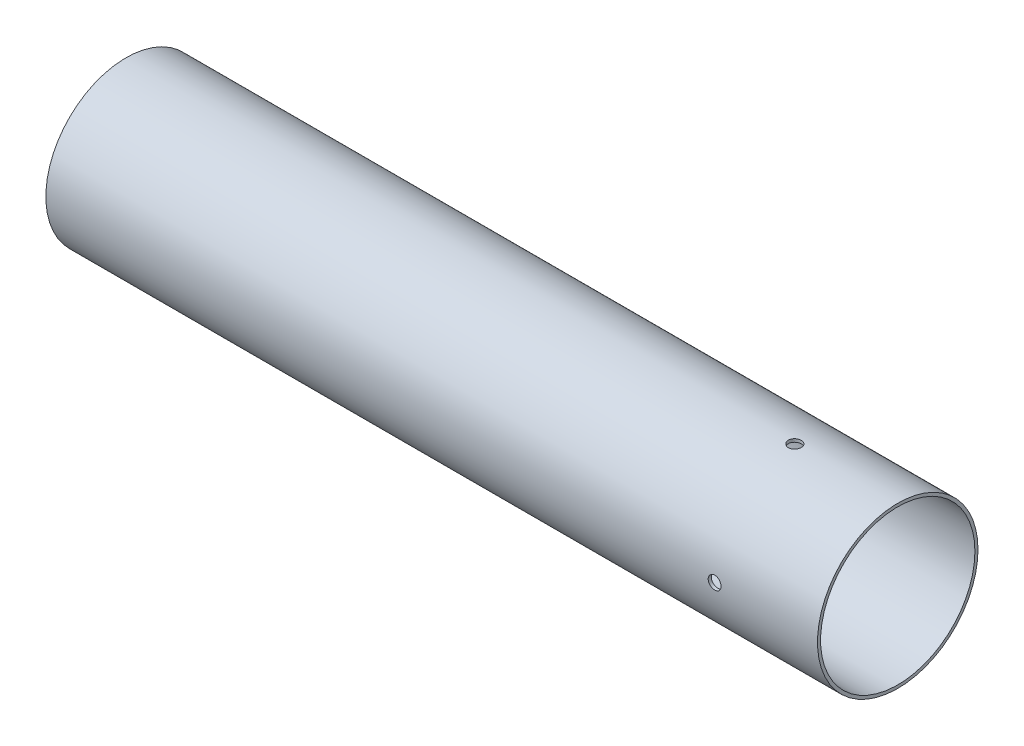
SolidWorks part; units mm, degrees
ref_plane "Front Plane" through (0, 0, 0) normal (1, 0, 0) x (0, 1, 0)
ref_plane "Top Plane" through (0, 0, 0) normal (0, 0, 1) x (0, 1, 0)
ref_plane "Right Plane" through (0, 0, 0) normal (0, 1, 0) x (-1, 0, 0)
sketch "Sketch1" plane through (0, 0, 0) normal (1, 0, 0) x (0, 1, 0)
  circle A0 centre (0, 0) radius 39.624
  circle A1 centre (0, 0) radius 38.1
  dimension "D1" = 79.248
  dimension "D2" = 76.2
extrude "Boss-Extrude1" add sketch "Sketch1" along normal blind 381
sketch "Sketch2" plane through (0, 0, 0) normal (0, 1, 0) x (-1, 0, 0)
  line L0 (-381, 39.624) -> (-381, -39.624) construction
  line L1 (-330.2, 0) -> (-381, 0) construction
  circle A0 centre (-330.2, 0) radius 3.175
  dimension "D1" = 6.35
  dimension "D2" = 50.8
extrude "Cut-Extrude1" cut sketch "Sketch2" along normal through all
pattern_circular "CirPattern1" count 4 over 360 about axis through (381, 0, 0) along (-1, 0, 0) of "Cut-Extrude1"
